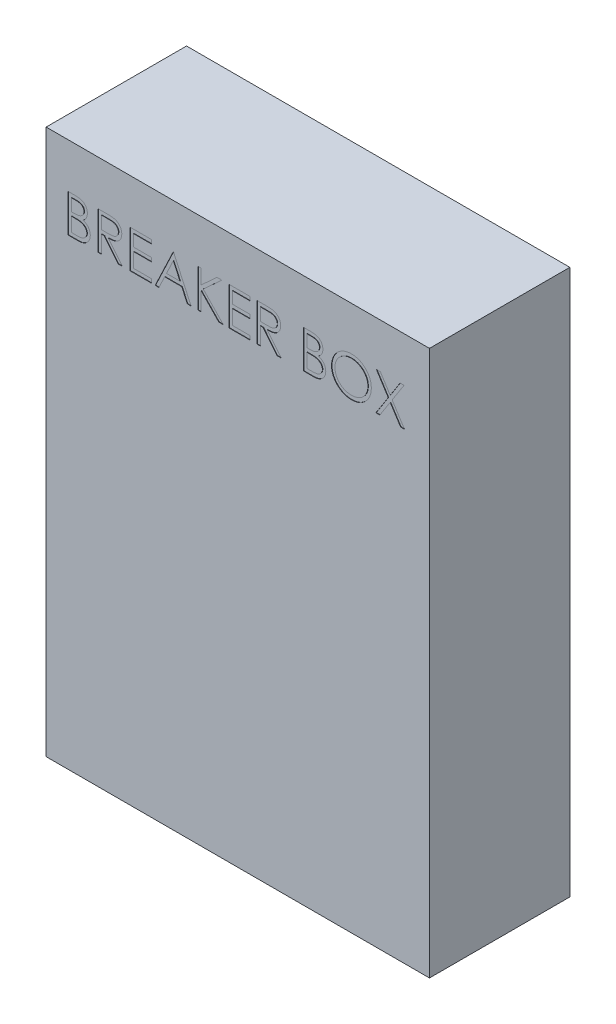
SolidWorks part; units mm, degrees
ref_plane "Front Plane" through (0, 0, 0) normal (0, 0, 1) x (1, 0, 0)
ref_plane "Top Plane" through (0, 0, 0) normal (0, 1, 0) x (1, 0, 0)
ref_plane "Right Plane" through (0, 0, 0) normal (1, 0, 0) x (0, 0, -1)
sketch "Sketch1" plane through (0, 0, 0) normal (0, 0, 1) x (1, 0, 0)
  line L1 (0, 0) -> (225.425, 0)
  line L2 (0, 0) -> (0, -320.675)
  line L3 (0, -320.675) -> (225.425, -320.675)
  line L4 (225.425, 0) -> (225.425, -320.675)
  dimension "D1" = 225.425
  dimension "D2" = 320.675
extrude "Boss-Extrude1" add sketch "Sketch1" against normal blind 82.55
sketch "Sketch2" plane through (0, 0, 0) normal (0, 0, 1) x (1, 0, 0)
  text T0 "BREAKER BOX" font "Century Gothic" height in points 84
extrude "Cut-Extrude1" cut sketch "Sketch2" against normal blind 0.254
